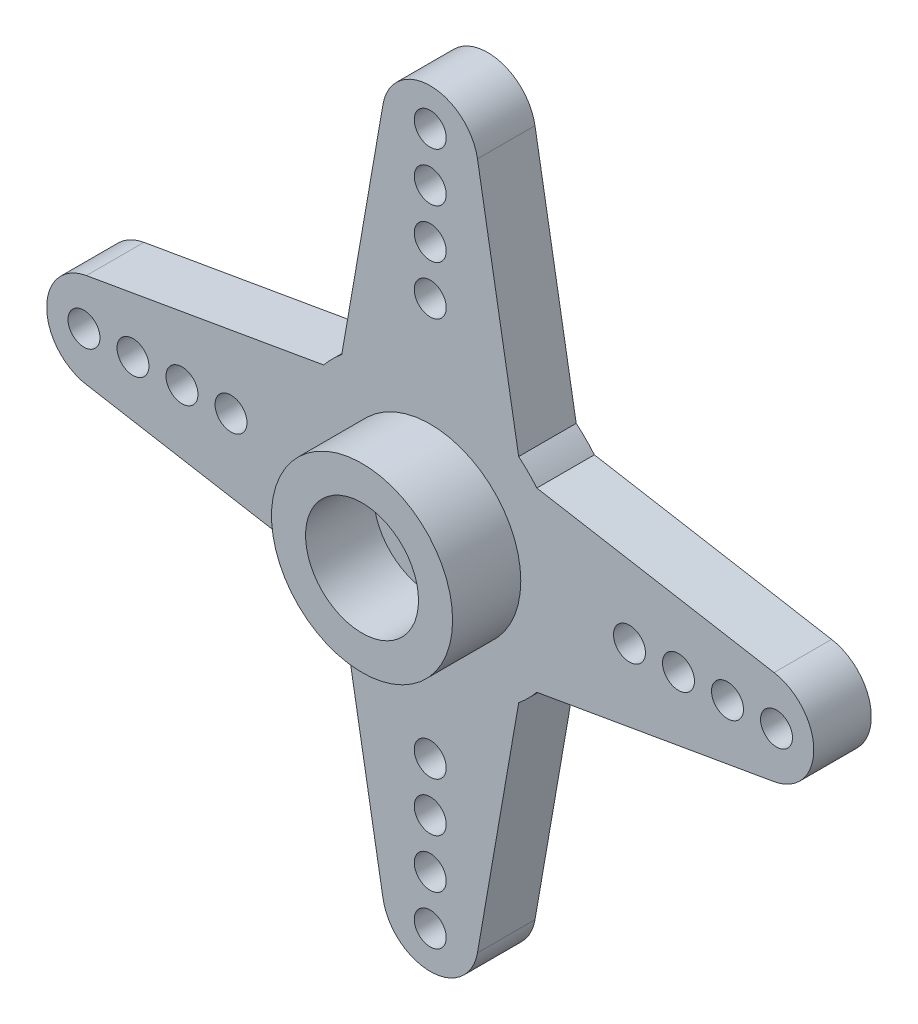
SolidWorks part; units mm, degrees
material "ABS"
ref_plane "Plano frontal" through (0, 0, 0) normal (0, 0, 1) x (1, 0, 0)
ref_plane "Plano superior" through (0, 0, 0) normal (0, 1, 0) x (1, 0, 0)
ref_plane "Plano direito" through (0, 0, 0) normal (1, 0, 0) x (0, 0, -1)
sketch "Esboço1" plane through (0, 0, 0) normal (0, 0, 1) x (1, 0, 0)
  line L0 (0, 15.75) -> (0, 0) construction
  line L1 (-2.2168, 16.135) -> (-4.15, 5.0027)
  line L3 (2.2168, 16.135) -> (4.15, 5.0027)
  arc A0 (-4.15, 5.0027) -> (4.15, 5.0027) centre (0, 0) ccw
  arc A1 (2.2168, 16.135) -> (-2.2168, 16.135) centre (0, 15.75) ccw
  circle A2 centre (0, 16.25) radius 0.75
  circle A3 centre (0, 13.95) radius 0.75
  circle A4 centre (0, 11.65) radius 0.75
  circle A5 centre (0, 9.35) radius 0.75
  circle A6 centre (0, 0) radius 1.5
  point P10 (0, 0)
  dimension "D1" = 13
  dimension "D2" = 18
  dimension "D3" = 4.5
  dimension "D4" = 1.5
  dimension "D7" = 3
  dimension "D8" = 4
  dimension "D5" = 8.3
  dimension "D6" = 16.25
extrude "Ressalto-extrusão1" add sketch "Esboço1" along normal blind 2.7
pattern_circular "PadrãoCircular1" count 4 over 360 about axis through (0, 0, 0) along (0, 0, 1) of "Ressalto-extrusão1"
sketch "Esboço2" plane through (0, 0, 2.7) normal (0, 0, 1) x (1, 0, 0)
  circle A0 centre (0, 0) radius 4.25
  circle A1 centre (0, 0) radius 2.65
  dimension "D1" = 8.5
  dimension "D2" = 1.6
extrude "Ressalto-extrusão2" add sketch "Esboço2" along normal blind 3.2
sketch "Esboço3" plane through (0, 0, 0) normal (0, 0, -1) x (-1, 0, 0)
  circle A0 centre (0, 0) radius 3.35
  circle A1 centre (0, 0) radius 2.85
  dimension "D1" = 6.7
  dimension "D2" = 0.5
extrude "Ressalto-extrusão3" add sketch "Esboço3" along normal blind 0.5
